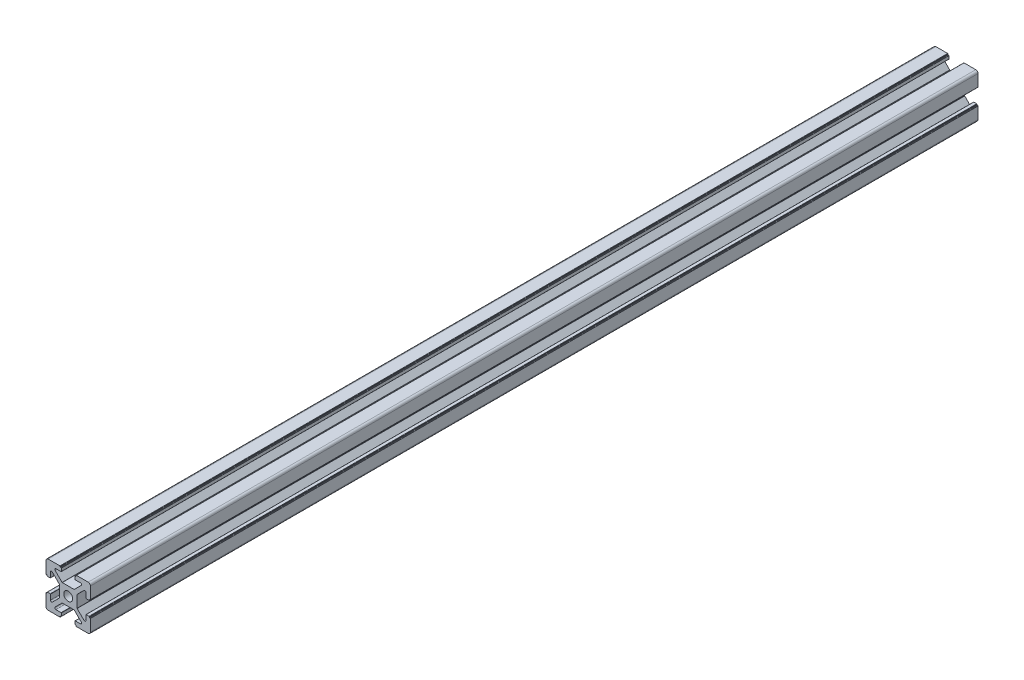
SolidWorks part; units mm, degrees
ref_plane "Plane1" through (0, 0, 0) normal (0, 0, 1) x (1, 0, 0)
ref_plane "Plane2" through (0, 0, 0) normal (0, 1, 0) x (1, 0, 0)
ref_plane "Plane3" through (0, 0, 0) normal (1, 0, 0) x (0, 0, -1)
sketch "Sketch1" plane through (0, 0, 0) normal (0, 0, 1) x (1, 0, 0)
  line L0 (-26.4662, 0) -> (25.1675, 0) construction
  line L1 (0, 16.7588) -> (0, -17.8201) construction
  line L2 (-10, 9) -> (-10, 3.7)
  line L3 (8, -5.5201) -> (8, -3.2)
  line L4 (-4, 0) -> (-4, 2.6858)
  line L5 (-2.6858, 4) -> (2.6858, 4)
  line L6 (4, 0) -> (4, 2.6858)
  line L7 (-4, -4) -> (4, 4) construction
  line L8 (-4, 4) -> (4, -4) construction
  line L9 (-9, 10) -> (-3.7, 10)
  line L10 (-8, 5.5201) -> (-8, 3.2)
  line L11 (10, -9) -> (10, -3.7)
  line L12 (9.6, -3.6) -> (9.9, -3.6)
  line L13 (-10, 10) -> (10, -10) construction
  line L14 (-10, -10) -> (10, 10) construction
  line L15 (9.5, -3.2) -> (9.5, -3.5)
  line L16 (8.1, -3.1) -> (9.4, -3.1)
  line L17 (-5.5201, 8) -> (-3.2, 8)
  line L18 (-7.1464, 5.8737) -> (-4.0293, 2.7565)
  line L19 (-5.8737, 7.1464) -> (-2.7565, 4.0293)
  line L20 (-3.1, 8.1) -> (-3.1, 9.4)
  line L21 (-3.2, 9.5) -> (-3.5, 9.5)
  line L22 (-3.6, 9.6) -> (-3.6, 9.9)
  line L23 (3.1, 8.1) -> (3.1, 9.4)
  line L24 (3.2, 9.5) -> (3.5, 9.5)
  line L25 (3.6, 9.6) -> (3.6, 9.9)
  line L26 (2.7565, 4.0293) -> (5.8737, 7.1464)
  line L27 (4.0293, 2.7565) -> (7.1464, 5.8737)
  line L28 (-8, 8) -> (8, 8) construction
  line L29 (-8, 8) -> (-8, -8) construction
  line L30 (8, 8) -> (8, -8) construction
  line L31 (3.7, 10) -> (9, 10)
  line L32 (-9, 10) -> (9, 10) construction
  line L33 (3.2, 8) -> (5.5201, 8)
  line L34 (-9.5, 3.2) -> (-9.5, 3.5)
  line L35 (-9.6, 3.6) -> (-9.9, 3.6)
  line L36 (-8.1, 3.1) -> (-9.4, 3.1)
  line L37 (-9, -10) -> (9, -10) construction
  line L38 (-10, 9) -> (-10, -9) construction
  line L39 (-8, -8) -> (8, -8) construction
  line L40 (10, 9) -> (10, -9) construction
  line L41 (8.1, 3.1) -> (9.4, 3.1)
  line L42 (9.5, 3.2) -> (9.5, 3.5)
  line L43 (9.6, 3.6) -> (9.9, 3.6)
  line L44 (10, 9) -> (10, 3.7)
  line L45 (8, 5.5201) -> (8, 3.2)
  line L46 (-8.1, -3.1) -> (-9.4, -3.1)
  line L47 (-9.6, -3.6) -> (-9.9, -3.6)
  line L48 (-9.5, -3.2) -> (-9.5, -3.5)
  line L49 (3.2, -8) -> (5.5201, -8)
  line L50 (3.7, -10) -> (9, -10)
  line L51 (4.0293, -2.7565) -> (7.1464, -5.8737)
  line L52 (2.7565, -4.0293) -> (5.8737, -7.1464)
  line L53 (3.6, -9.6) -> (3.6, -9.9)
  line L54 (3.2, -9.5) -> (3.5, -9.5)
  line L55 (3.1, -8.1) -> (3.1, -9.4)
  line L56 (-3.6, -9.6) -> (-3.6, -9.9)
  line L57 (-3.2, -9.5) -> (-3.5, -9.5)
  line L58 (-3.1, -8.1) -> (-3.1, -9.4)
  line L59 (-5.8737, -7.1464) -> (-2.7565, -4.0293)
  line L60 (-7.1464, -5.8737) -> (-4.0293, -2.7565)
  line L61 (-5.5201, -8) -> (-3.2, -8)
  line L62 (-8, -5.5201) -> (-8, -3.2)
  line L63 (-9, -10) -> (-3.7, -10)
  line L64 (-2.6858, -4) -> (2.6858, -4)
  line L65 (-10, -9) -> (-10, -3.7)
  line L66 (-4, 0) -> (-4, -2.6858)
  line L68 (4, 0) -> (4, -2.6858)
  circle A0 centre (0, 0) radius 2
  arc A1 (-10, 9) -> (-9, 10) centre (-9, 9) cw
  arc A2 (10, -3.7) -> (9.9, -3.6) centre (9.9, -3.7) ccw
  arc A3 (-10, -9) -> (-9, -10) centre (-9, -9) ccw construction
  arc A4 (10, 9) -> (9, 10) centre (9, 9) ccw
  arc A5 (-8, -8) -> (-8, -8) centre (-8, -8) ccw
  arc A6 (8, -8) -> (8, -8) centre (8, -8) cw
  arc A7 (8, 8) -> (8, 8) centre (8, 8) ccw
  arc A8 (-8, 8) -> (-8, 8) centre (-8, 8) cw
  arc A9 (-5.5201, 8) -> (-5.8737, 7.1464) centre (-5.5201, 7.5) ccw
  arc A10 (5.5201, 8) -> (5.8737, 7.1464) centre (5.5201, 7.5) cw
  arc A11 (-8, 5.5201) -> (-7.1464, 5.8737) centre (-7.5, 5.5201) cw
  arc A12 (8, 5.5201) -> (7.1464, 5.8737) centre (7.5, 5.5201) ccw
  arc A13 (-3.6, 9.9) -> (-3.7, 10) centre (-3.7, 9.9) ccw
  arc A14 (-3.5, 9.5) -> (-3.6, 9.6) centre (-3.5, 9.6) cw
  arc A15 (-3.2, 9.5) -> (-3.1, 9.4) centre (-3.2, 9.4) cw
  arc A16 (-3.1, 8.1) -> (-3.2, 8) centre (-3.2, 8.1) cw
  arc A17 (3.2, 8) -> (3.1, 8.1) centre (3.2, 8.1) cw
  arc A18 (3.2, 9.5) -> (3.1, 9.4) centre (3.2, 9.4) ccw
  arc A19 (3.5, 9.5) -> (3.6, 9.6) centre (3.5, 9.6) ccw
  arc A20 (3.7, 10) -> (3.6, 9.9) centre (3.7, 9.9) ccw
  arc A21 (-2.6858, 4) -> (-2.7565, 4.0293) centre (-2.6858, 4.1) cw
  arc A22 (-4, 2.6858) -> (-4.0293, 2.7565) centre (-4.1, 2.6858) ccw
  arc A23 (2.6858, 4) -> (2.7565, 4.0293) centre (2.6858, 4.1) ccw
  arc A24 (4.0293, 2.7565) -> (4, 2.6858) centre (4.1, 2.6858) ccw
  arc A25 (-9.5, 3.2) -> (-9.4, 3.1) centre (-9.4, 3.2) ccw
  arc A26 (-9.5, 3.5) -> (-9.6, 3.6) centre (-9.6, 3.5) ccw
  arc A27 (-9.9, 3.6) -> (-10, 3.7) centre (-9.9, 3.7) cw
  arc A28 (-8.1, 3.1) -> (-8, 3.2) centre (-8.1, 3.2) ccw
  arc A29 (8, 3.2) -> (8.1, 3.1) centre (8.1, 3.2) ccw
  arc A30 (9.5, 3.2) -> (9.4, 3.1) centre (9.4, 3.2) cw
  arc A31 (9.5, 3.5) -> (9.6, 3.6) centre (9.6, 3.5) cw
  arc A32 (10, 3.7) -> (9.9, 3.6) centre (9.9, 3.7) cw
  arc A33 (10, -9) -> (9, -10) centre (9, -9) cw construction
  arc A34 (9.5, -3.5) -> (9.6, -3.6) centre (9.6, -3.5) ccw
  arc A35 (9.5, -3.2) -> (9.4, -3.1) centre (9.4, -3.2) ccw
  arc A36 (8, -3.2) -> (8.1, -3.1) centre (8.1, -3.2) cw
  arc A37 (-8.1, -3.1) -> (-8, -3.2) centre (-8.1, -3.2) cw
  arc A38 (-9.9, -3.6) -> (-10, -3.7) centre (-9.9, -3.7) ccw
  arc A39 (-9.5, -3.5) -> (-9.6, -3.6) centre (-9.6, -3.5) cw
  arc A40 (-9.5, -3.2) -> (-9.4, -3.1) centre (-9.4, -3.2) cw
  arc A41 (4.0293, -2.7565) -> (4, -2.6858) centre (4.1, -2.6858) cw
  arc A42 (2.6858, -4) -> (2.7565, -4.0293) centre (2.6858, -4.1) cw
  arc A43 (-4, -2.6858) -> (-4.0293, -2.7565) centre (-4.1, -2.6858) cw
  arc A44 (-2.6858, -4) -> (-2.7565, -4.0293) centre (-2.6858, -4.1) ccw
  arc A45 (3.7, -10) -> (3.6, -9.9) centre (3.7, -9.9) cw
  arc A46 (3.5, -9.5) -> (3.6, -9.6) centre (3.5, -9.6) cw
  arc A47 (3.2, -9.5) -> (3.1, -9.4) centre (3.2, -9.4) cw
  arc A48 (3.2, -8) -> (3.1, -8.1) centre (3.2, -8.1) ccw
  arc A49 (-3.1, -8.1) -> (-3.2, -8) centre (-3.2, -8.1) ccw
  arc A50 (-3.2, -9.5) -> (-3.1, -9.4) centre (-3.2, -9.4) ccw
  arc A51 (-3.5, -9.5) -> (-3.6, -9.6) centre (-3.5, -9.6) ccw
  arc A52 (-3.6, -9.9) -> (-3.7, -10) centre (-3.7, -9.9) cw
  arc A53 (8, -5.5201) -> (7.1464, -5.8737) centre (7.5, -5.5201) cw
  arc A54 (-8, -5.5201) -> (-7.1464, -5.8737) centre (-7.5, -5.5201) ccw
  arc A55 (5.5201, -8) -> (5.8737, -7.1464) centre (5.5201, -7.5) ccw
  arc A56 (-5.5201, -8) -> (-5.8737, -7.1464) centre (-5.5201, -7.5) cw
  arc A57 (10, -9) -> (9, -10) centre (9, -9) cw
  arc A58 (-10, -9) -> (-9, -10) centre (-9, -9) ccw
  point P0 (0, 0)
  point P70 (3.1, 8.75)
  point P72 (-3.6, 10)
  point P75 (-3.6, 9.5)
  point P82 (3.1, 8)
  point P87 (3.6, 9.5)
  point P90 (3.6, 10)
  point P198 (3.6, -10)
  point P199 (3.6, -9.5)
  point P200 (3.1, -8)
  point P201 (-3.6, -9.5)
  point P202 (-3.6, -10)
extrude "Boss-Extrude1" add sketch "Sketch1" along normal blind 400 contours L65 A58 L63 A52 L56 A51 L57 A50 L58 A49 L61 A56 L59 A44 L64 A42 L52 A55 L49 A48 L55 A47 L54 A46 L53 A45 L50 A57 L11 A2 L12 A34 L15 A35 L16 A36 L3 A53 L51 A41 L68 L6 A24 L27 A12 L45 A29 L41 A30 L42 A31
